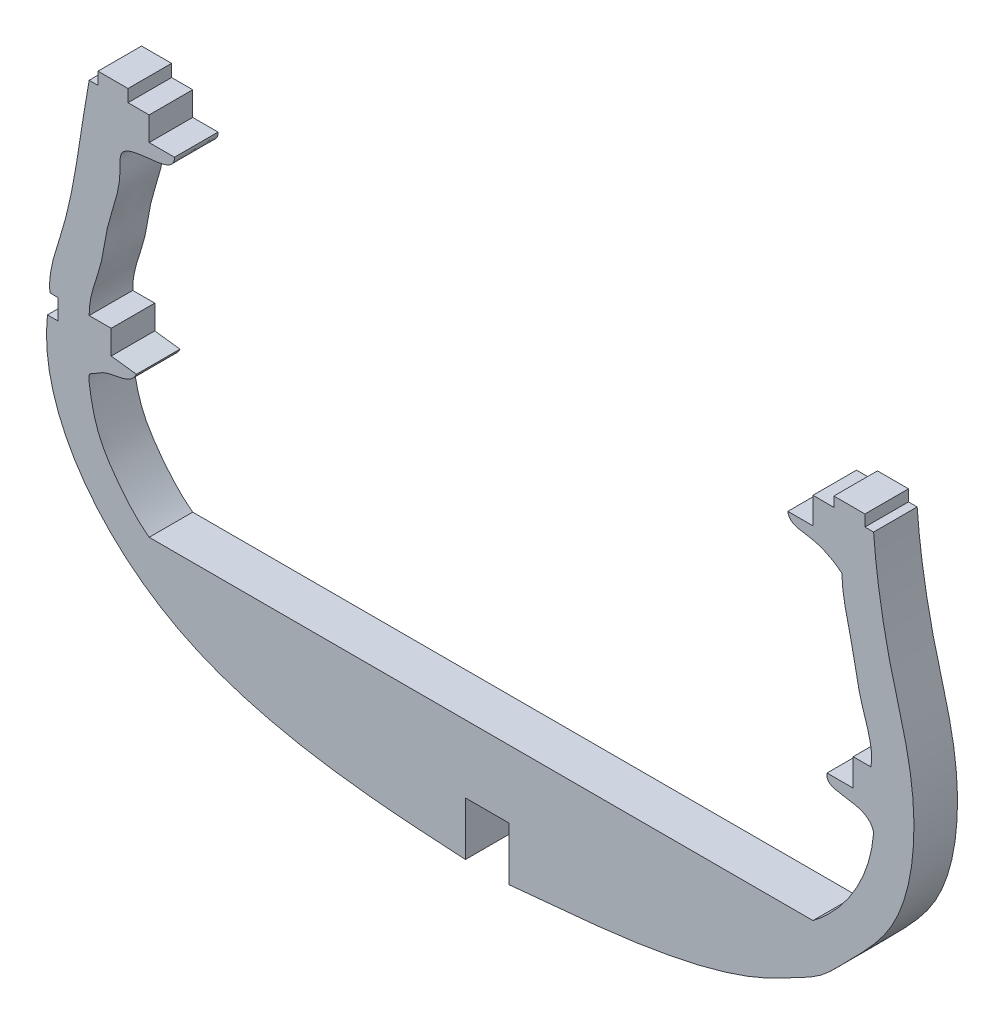
SolidWorks part; units mm, degrees
ref_plane "前视基准面" through (0, 0, 0) normal (0, 0, 1) x (1, 0, 0)
ref_plane "上视基准面" through (0, 0, 0) normal (0, 1, 0) x (1, 0, 0)
ref_plane "右视基准面" through (0, 0, 0) normal (1, 0, 0) x (0, 0, -1)
other "Configuration Table"
sketch "草图1" plane through (0, 0, 0) normal (0, 0, 1) x (1, 0, 0)
  line L0 (376.5, 617) -> (1882.5, 617) construction
  line L66 (0, 0) -> (121.8929, 0)
  line L67 (124.4777, 24.7572) -> (129.2829, 24.7572)
  line L68 (129.2829, 24.7572) -> (129.2829, 29.7553)
  line L69 (129.2829, 29.7553) -> (132.5262, 29.7553)
  line L70 (117.2806, 62.7701) -> (121.8929, 62.7701)
  line L71 (121.8929, 62.7701) -> (121.8929, 67.6302)
  line L72 (121.8929, 67.6302) -> (125.7329, 67.6302)
  line L73 (125.7329, 67.6302) -> (125.7329, 69.4304)
  line L74 (125.7329, 69.4304) -> (131.4386, 69.4304)
  line L75 (131.4386, 69.4304) -> (131.4386, 67.3495)
  line L76 (131.4386, 67.3495) -> (133.0292, 67.3495)
  line L80 (-18.2238, 29.7553) -> (-16.7525, 29.7553)
  line L81 (-16.7525, 29.7553) -> (-16.7525, 26.0369)
  line L82 (-16.7525, 26.0369) -> (-18.6763, 26.0369)
  line L83 (-11.0148, 67.1726) -> (-9.3965, 67.1726)
  line L84 (-9.3965, 67.1726) -> (-9.3965, 69.4304)
  line L85 (-9.3965, 69.4304) -> (-3.8794, 69.4304)
  line L86 (-3.8794, 69.4304) -> (-3.8794, 67.1726)
  line L87 (-3.8794, 67.1726) -> (0, 67.1726)
  line L88 (0, 67.1726) -> (0, 62.7701)
  line L89 (0, 62.7701) -> (4.6536, 62.7701)
  line L90 (-11.0148, 29.7553) -> (-6.969, 29.7553)
  line L91 (-6.969, 29.7553) -> (-6.969, 25.3386)
  line L92 (-6.969, 25.3386) -> (-2.3347, 24.7572)
  line L93 (58.0819, -12.405) -> (66.0819, -12.405)
  line L94 (58.0819, -12.405) -> (58.0819, -22.205)
  line L96 (66.0819, -12.405) -> (66.0819, -22.205)
  spline S25 degree 3 poles (121.8929, 0) (128.012, 4.6018) (132.4545, 11.7883) (133.0292, 19.5054) knots 0 0 0 0 1 1 1 1
  spline S26 degree 3 poles (133.0292, 19.5054) (132.4579, 22.0406) (128.4992, 22.3456) (124.2078, 23.2177) (124.4777, 24.7572) knots 0 0 0 0 0.647424 1 1 1 1
  spline S27 degree 3 poles (132.5262, 29.7553) (133.1095, 33.2105) (130.536, 38.4842) (129.1829, 47.9778) (127.2743, 53.9267) (127.1926, 57.9184) knots 0 0 0 0 0.352753 0.588696 1 1 1 1
  spline S28 degree 3 poles (117.2806, 62.7701) (117.4756, 61.0677) (122.2095, 60.8443) (125.1447, 59.5069) (127.1926, 57.9184) knots 0 0 0 0 0.387326 1 1 1 1
  spline S29 degree 3 poles (133.0292, 67.3495) (133.5649, 60.2476) (135.3982, 49.2458) (140.0677, 33.723) (141.072, 19.8196) (137.2815, 5.3434) (129.1446, -2.2581) (123.3083, -8.4319) (118.3036, -10.8582) (111.5874, -14.4564) (94.638, -20.0191) (78.3484, -21.0081) (66.0819, -22.205) knots 0 0 0 0 0.151238 0.23603 0.343539 0.44464 0.540293 0.575127 0.624227 0.656634 0.737279 1 1 1 1
  spline S30 degree 3 poles (58.0819, -22.205) (46.0685, -21.5338) (26.7497, -20.3005) (-5.2784, -9.189) (-20.325, 11.1177) (-18.6763, 26.0369) knots 0 0 0 0 0.358877 0.569205 1 1 1 1
  spline S31 degree 3 poles (-18.2238, 29.7553) (-18.5505, 33.449) (-13.7569, 45.3431) (-12.6988, 58.2183) (-11.0148, 67.1726) knots 0 0 0 0 0.27932 1 1 1 1
  spline S32 degree 3 poles (-11.0148, 29.7553) (-11.0942, 33.2146) (-8.7613, 37.7591) (-8.0844, 43.9583) (-6.6371, 49.2616) (-5.0488, 53.6845) (-5.8553, 61.8154) (4.752, 59.0267) (4.6536, 62.7701) knots 0 0 0 0 0.254341 0.369748 0.466004 0.663215 0.735185 1 1 1 1
  spline S33 degree 3 poles (0, 0) (-2.7068, 1.9855) (-7.9077, 8.4558) (-10.1378, 13.0537) (-11.3283, 20.9046) (-10.3292, 20.763) (-8.9369, 21.6731) knots 0 0 0 0 0.369244 0.820134 0.903852 1 1 1 1
  spline S34 degree 3 poles (-8.9369, 21.6731) (-6.945, 23.0347) (-3.5485, 22.1193) (-2.3347, 24.7572) knots 0 0 0 0 1 1 1 1
  dimension "D1" = 8
  dimension "D2" = 9.8
extrude "凸台-拉伸1" add sketch "草图1" along normal blind 8
